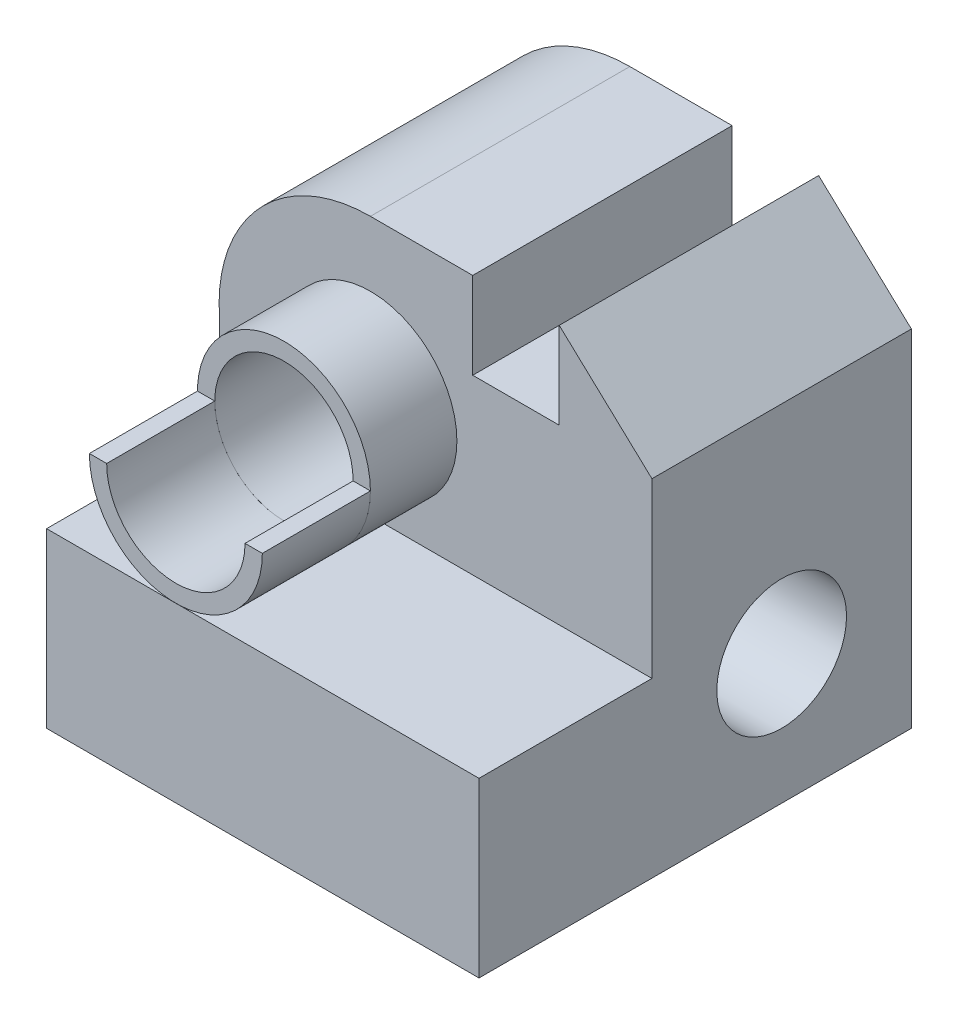
SolidWorks part; units mm, degrees
ref_plane "Front Plane" through (0, 0, 0) normal (0, 0, 1) x (1, 0, 0)
ref_plane "Top Plane" through (0, 0, 0) normal (0, 1, 0) x (1, 0, 0)
ref_plane "Right Plane" through (0, 0, 0) normal (1, 0, 0) x (0, 0, -1)
sketch "Sketch1" plane through (0, 0, 0) normal (0, 0, 1) x (1, 0, 0)
  line L0 (-25.9531, 0) -> (37.5469, 0)
  line L1 (37.5469, 0) -> (37.5469, 25.4)
  line L2 (37.5469, 25.4) -> (-25.9531, 25.4)
  line L3 (-25.9531, 25.4) -> (-25.9531, 0)
  dimension "D1" = 63.5
  dimension "D2" = 25.4
extrude "Boss-Extrude1" add sketch "Sketch1" against normal blind 63.5
sketch "Sketch2" plane through (0, 0, -63.5) normal (0, 0, -1) x (-1, 0, 0)
  line L0 (-37.5469, 25.4) -> (-37.5469, 50.8)
  line L1 (-37.5469, 50.8) -> (-23.9278, 63.5)
  line L2 (-23.9278, 63.5) -> (-23.9278, 50.8)
  line L3 (-23.9278, 50.8) -> (-11.2278, 50.8)
  line L4 (-11.2278, 50.8) -> (-11.2278, 63.5)
  line L5 (-11.2278, 63.5) -> (3.7989, 63.5)
  line L6 (25.9531, 25.4) -> (25.9531, 39.5023)
  line L7 (-37.5469, 25.4) -> (25.9531, 25.4)
  arc A0 (3.7989, 63.5) -> (25.9531, 39.5023) centre (3.7989, 41.275) cw
  dimension "D7" = 22.225
  dimension "D1" = 50.8
  dimension "D2" = 12.7
  dimension "D3" = 133
  dimension "D4" = 12.7
  dimension "D5" = 12.7
  dimension "D6" = 12.7
extrude "Boss-Extrude2" add sketch "Sketch2" against normal blind 38.1
sketch "Sketch3" plane through (0, 0, -25.4) normal (0, 0, 1) x (1, 0, 0)
  line L0 (-16.4989, 41.275) -> (8.9011, 41.275)
  circle A0 centre (-3.7989, 41.275) radius 12.7
  circle A1 centre (-3.7989, 41.275) radius 10.16
  dimension "D1" = 2.54
extrude "Boss-Extrude3" add sketch "Sketch3" along normal blind 12.7 contours A1 L0 A0 | A1 L0 A0
sketch "Sketch4" plane through (0, 0, -12.7) normal (0, 0, 1) x (1, 0, 0)
  line L0 (-16.4989, 41.275) -> (8.9011, 41.275)
  line L2 (-13.9589, 41.275) -> (6.3611, 41.275)
  arc A0 (-16.4989, 41.275) -> (8.9011, 41.275) centre (-3.7989, 41.275) ccw
  arc A2 (-13.9589, 41.275) -> (6.3611, 41.275) centre (-3.7989, 41.275) ccw
extrude "Boss-Extrude4" add sketch "Sketch4" along normal blind 15.875 separate body
sketch "Sketch5" plane through (0, 0, -25.4) normal (0, 0, 1) x (1, 0, 0)
  circle A0 centre (-3.7989, 41.275) radius 10.16
extrude "Cut-Extrude1" cut sketch "Sketch5" against normal through all
sketch "Sketch6" plane through (37.5469, 0, 0) normal (1, 0, 0) x (0, 0, -1)
  line L0 (63.5, 0) -> (63.5, 50.8) construction
  line L1 (63.5, 0) -> (0, 0) construction
  circle A0 centre (44.45, 19.05) radius 9.525
  dimension "D1" = 19.05
  dimension "D2" = 19.05
extrude "Cut-Extrude2" cut sketch "Sketch6" against normal through all
